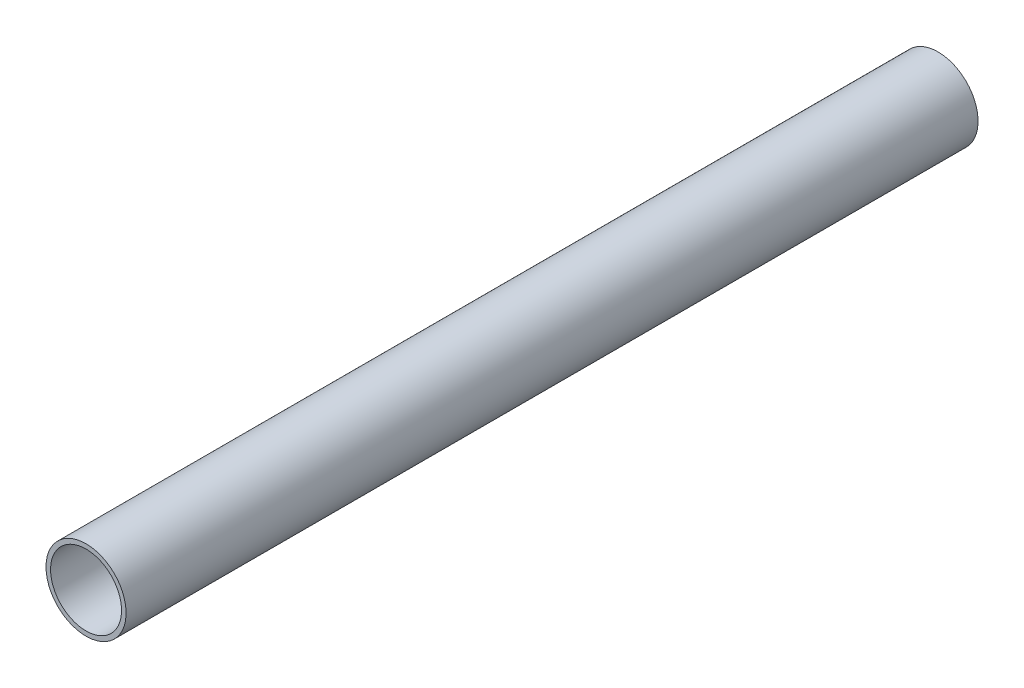
SolidWorks part; units mm, degrees
ref_plane "Front Plane" through (0, 0, 0) normal (0, 0, 1) x (1, 0, 0)
ref_plane "Top Plane" through (0, 0, 0) normal (0, 1, 0) x (1, 0, 0)
ref_plane "Right Plane" through (0, 0, 0) normal (1, 0, 0) x (0, 0, -1)
sketch "Sketch1" plane through (0, 0, 0) normal (0, 0, 1) x (1, 0, 0)
  circle A0 centre (0, 0) radius 14.3256 construction
  circle A1 centre (0, 0) radius 12.7 construction
  point P4 (12.7, 0)
  point P5 (14.3256, 0)
  dimension "OD" = 28.6512
  dimension "ID" = 25.4
  dimension "Wall Thickness" = 1.6256
sketch "Sketch2" plane through (0, 0, 0) normal (1, 0, 0) x (0, 0, -1)
  line L0 (-152.4, 0) -> (152.4, 0) construction
  line L1 (-152.4, -14.3256) -> (-152.4, 14.3256) construction
  line L2 (-152.4, 14.3256) -> (152.4, 14.3256) construction
  line L3 (152.4, -14.3256) -> (152.4, 14.3256) construction
  line L5 (-152.4, -14.3256) -> (152.4, -14.3256) construction
  point P0 (-123.7488, 0)
  point P3 (0, 0)
  point P7 (0, 14.3256)
  point P8 (123.7488, 0)
  point P11 (-152.4, 0)
  point P13 (152.4, 0)
  dimension "Length" = 304.8
  dimension "D1" = 28.6512
  dimension "D2" = 28.6512
sketch "Sketch3" plane through (0, 0, 0) normal (0, 0, 1) x (1, 0, 0)
  circle A0 centre (0, 0) radius 12.7 construction
  circle A1 centre (0, 0) radius 14.3256 construction
  circle A2 centre (0, 0) radius 12.7
  circle A3 centre (0, 0) radius 14.3256
extrude "Boss-Extrude1" add sketch "Sketch3" along normal up to vertex (152.4 mm away) and the other way up to vertex (152.4 mm away) up to point (0, 0, 152.4) other way up to point (0, 0, -152.4)
equation "\"D1@Sketch2\"=\"OD@Sketch1\""
equation "\"D2@Sketch2\"=\"D1@Sketch2\""
